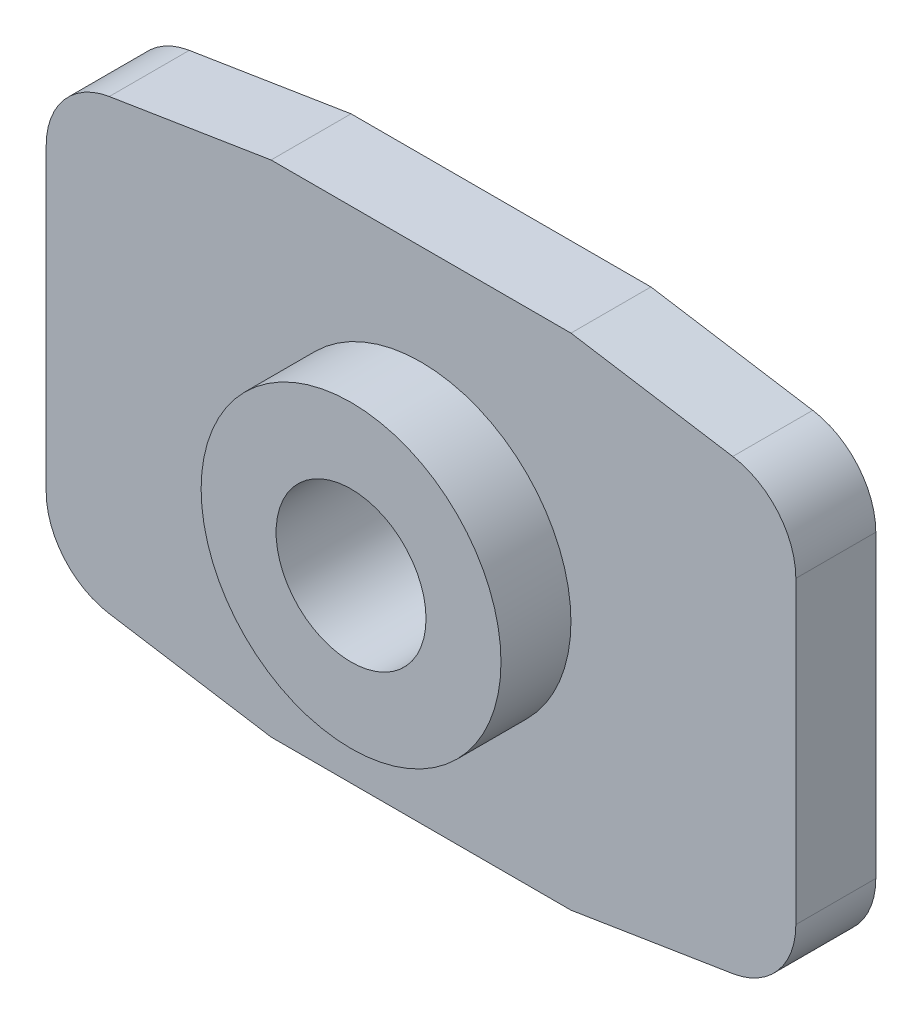
SolidWorks part; units mm, degrees
material "Plain Carbon Steel"
ref_plane "Front Plane" through (0, 0, 0) normal (0, 0, 1) x (1, 0, 0)
ref_plane "Top Plane" through (0, 0, 0) normal (0, 1, 0) x (1, 0, 0)
ref_plane "Right Plane" through (0, 0, 0) normal (1, 0, 0) x (0, 0, -1)
sketch "Sketch1" plane through (0, 0, 0) normal (0, 0, 1) x (1, 0, 0)
  line L0 (-7.5, 0) -> (7.5, 0) construction
  line L1 (-6.2374, 4.4811) -> (-3, 5)
  line L2 (-7.5, -3) -> (-7.5, 3)
  line L3 (-3, 5) -> (3, 5)
  line L4 (7.5, -3) -> (7.5, 3)
  line L5 (0, 5) -> (0, 0) construction
  line L6 (6.2374, 4.4811) -> (3, 5)
  line L7 (6.2374, -4.4811) -> (3, -5)
  line L8 (-3, -5) -> (3, -5)
  line L9 (-6.2374, -4.4811) -> (-3, -5)
  arc A0 (7.5, 3) -> (6.2374, 4.4811) centre (6, 3) ccw
  arc A1 (-7.5, -3) -> (-6.2374, -4.4811) centre (-6, -3) ccw
  arc A2 (7.5, -3) -> (6.2374, -4.4811) centre (6, -3) cw
  arc A3 (-7.5, 3) -> (-6.2374, 4.4811) centre (-6, 3) cw
  dimension "D3" = 6
  dimension "D5" = 1.5
  dimension "D1" = 15
  dimension "D2" = 10
  dimension "D4" = 6
extrude "Boss-Extrude1" add sketch "Sketch1" along normal blind 1.6
sketch "Sketch2" plane through (0, 0, 1.6) normal (0, 0, 1) x (1, 0, 0)
  line L0 (-7.5, 0) -> (0, 0) construction
  line L1 (-7.5, 3) -> (-7.5, -3) construction
  line L2 (0, 0) -> (0, 5) construction
  line L4 (3, 5) -> (-3, 5) construction
  circle A0 centre (0, 0) radius 3
  dimension "D2" = 6
extrude "Boss-Extrude2" add sketch "Sketch2" along normal blind 1.4
hole_wizard "M5x0.8 Tapped Hole1" positions "Sketch4" profile "Sketch3" tap size "M5x0.8" standard "ANSI Metric" end condition through all
sketch "Sketch4" plane through (0, 0, 3) normal (0, 0, 1) x (1, 0, 0)
  point P0 (0, 0)
sketch "Sketch3" plane through (0, 0, 3) normal (1, 0, 0) x (0, -1, 0)
  line L0 (0, 0) -> (0, 3)
  line L1 (0, 3) -> (1.5, 3)
  line L2 (1.5, 3) -> (1.5, 0)
  line L5 (1.5, 0) -> (0, 0)
  line L11 (0, -6.35) -> (0, 107.95) construction
  dimension "Thread Major Dia." = 3
  dimension "Thru Tap Drill Depth" = 3
